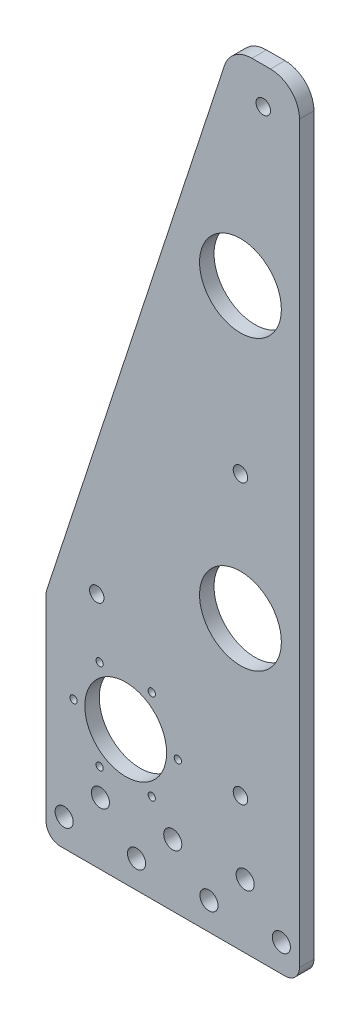
SolidWorks part; units mm, degrees
material "PC High Viscosity"
ref_plane "Front Plane" through (0, 0, 0) normal (0, 0, 1) x (1, 0, 0)
ref_plane "Top Plane" through (0, 0, 0) normal (0, 1, 0) x (1, 0, 0)
ref_plane "Right Plane" through (0, 0, 0) normal (1, 0, 0) x (0, 0, -1)
sketch "Sketch1" plane through (0, 0, 0) normal (0, 0, 1) x (1, 0, 0)
  line L2 (88.9, 212.09) -> (88.9, 5.08)
  line L3 (83.82, 0) -> (5.08, 0)
  line L4 (78.74, 222.25) -> (55.6253, 222.25)
  line L5 (45.9692, 215.25) -> (0.252, 75.55)
  line L6 (0, 73.97) -> (0, 5.08)
  line L7 (6.35, 9.652) -> (31.75, 9.652) construction
  line L8 (27.94, 46.99) -> (27.94, 82.7405) construction
  line L9 (27.94, 46.99) -> (60.7143, 46.99) construction
  circle A0 centre (68.199, 201.93) radius 14.351
  circle A1 centre (68.199, 100.838) radius 14.351
  circle A2 centre (68.199, 144.78) radius 2.54
  circle A3 centre (68.199, 46.99) radius 2.54
  arc A4 (78.74, 222.25) -> (88.9, 212.09) centre (78.74, 212.09) cw
  arc A5 (0, 5.08) -> (5.08, 0) centre (5.08, 5.08) ccw
  arc A6 (88.9, 5.08) -> (83.82, 0) centre (83.82, 5.08) cw
  arc A7 (55.6253, 222.25) -> (45.9692, 215.25) centre (55.6253, 212.09) ccw
  arc A8 (0.252, 75.55) -> (0, 73.97) centre (5.08, 73.97) ccw
  circle A9 centre (27.94, 46.99) radius 14.351
  circle A17 centre (68.199, 201.93) radius 50.8 construction
  circle A18 centre (68.199, 100.838) radius 38.1 construction
  circle A19 centre (6.35, 9.652) radius 3.175
  circle A21 centre (31.75, 9.652) radius 3.175
  circle A22 centre (57.15, 9.652) radius 3.175
  circle A23 centre (82.55, 9.652) radius 3.175
  circle A29 centre (69.85, 22.352) radius 3.175
  circle A30 centre (44.45, 21.844) radius 3.175
  circle A31 centre (19.05, 21.844) radius 3.175
  circle A32 centre (46.228, 46.99) radius 1.27
  circle A38 centre (37.084, 31.1521) radius 1.27
  circle A39 centre (18.796, 31.1521) radius 1.27
  circle A40 centre (9.652, 46.99) radius 1.27
  circle A41 centre (18.796, 62.8279) radius 1.27
  circle A42 centre (37.084, 62.8279) radius 1.27
  point P17 (88.9, 222.25)
  point P20 (0, 0)
  point P23 (88.9, 0)
  point P25 (48.26, 222.25)
  point P26 (48.26, 222.25)
  point P43 (27.94, 46.99)
  point P69 (27.94, 46.99)
  dimension "D1" = 28.702
  dimension "D2" = 28.702
  dimension "D4" = 88.9
  dimension "D7" = 5.08
  dimension "D9" = 5.08
  dimension "D11" = 10.16
  dimension "D12" = 5.08
  dimension "D13" = 10.16
  dimension "D14" = 5.08
  dimension "D16" = 28.702
  dimension "D17" = 18.288
  dimension "D23" = 139.7
  dimension "D24" = 101.6
  dimension "D25" = 76.2
  dimension "D26" = 6.35
  dimension "D29" = 21.844
  dimension "D31" = 6.35
  dimension "D32" = 4
  dimension "D34" = 19.05
  dimension "D39" = 21.844
  dimension "D30" = 6.35
  dimension "D35" = 6.35
  dimension "D37" = 6.35
  dimension "D38" = 25.4
  dimension "D18" = 2.54
  dimension "D3" = 101.092
  dimension ".75" = 20.701
  dimension "D5" = 222.25
  dimension "D6" = 20.32
  dimension "D8" = 57.15
  dimension "D10" = 97.79
  dimension "D15" = 40.64
  dimension "D20" = 27.94
  dimension "D21" = 9.144
  dimension "D22" = 15.8379
  dimension "D27" = 9.652
  dimension "D28" = 25.4
  dimension "D33" = 12.7
  dimension "D36" = 25.4
  dimension "D19" = 6
extrude "Boss-Extrude1" add sketch "Sketch1" along normal blind 5.08
sketch "Sketch2" plane through (0, 0, 5.08) normal (0, 0, 1) x (1, 0, 0)
  line L0 (45.9692, 215.25) -> (62.5937, 266.05)
  line L1 (45.9692, 215.25) -> (0.252, 75.55) construction
  line L2 (72.2498, 273.05) -> (78.74, 273.05)
  line L3 (88.9, 262.89) -> (88.9, 212.09)
  line L4 (78.74, 222.25) -> (55.6253, 222.25) construction
  line L5 (45.9692, 215.25) -> (55.6253, 222.25)
  line L6 (55.6253, 222.25) -> (78.74, 222.25)
  line L7 (78.74, 222.25) -> (88.9, 212.09)
  line L8 (76.2, 156.304) -> (76.2, 48.354) construction
  line L9 (88.9, 5.08) -> (88.9, 212.09) construction
  arc A0 (78.74, 273.05) -> (88.9, 262.89) centre (78.74, 262.89) cw
  arc A1 (62.5937, 266.05) -> (72.2498, 273.05) centre (72.2498, 262.89) cw
  circle A2 centre (76.2, 260.35) radius 2.54
  point P19 (68.199, 144.78)
  point P26 (68.199, 156.304)
  dimension "D2" = 10.16
  dimension "D3" = 5.08
  dimension "D1" = 50.8
  dimension "D4" = 12.7
  dimension "D5" = 12.7
extrude "Boss-Extrude2" add sketch "Sketch2" against normal blind 5.08 contours L2 A0 L3 L7 L6 L5 L0 A1
sketch "Sketch3" plane through (0, 0, 5.08) normal (0, 0, 1) x (1, 0, 0)
  line L0 (68.199, 83.058) -> (-39.9215, 83.058) construction
  line L1 (17.78, 46.99) -> (17.78, -14.087) construction
  circle A1 centre (17.78, 83.058) radius 2.54
  point P0 (68.199, 100.838)
  point P2 (27.94, 46.99)
  dimension "D1" = 5.08
  dimension "D2" = 10.16
  dimension "D3" = 17.78
extrude "Cut-Extrude1" cut sketch "Sketch3" against normal through all contours A1
